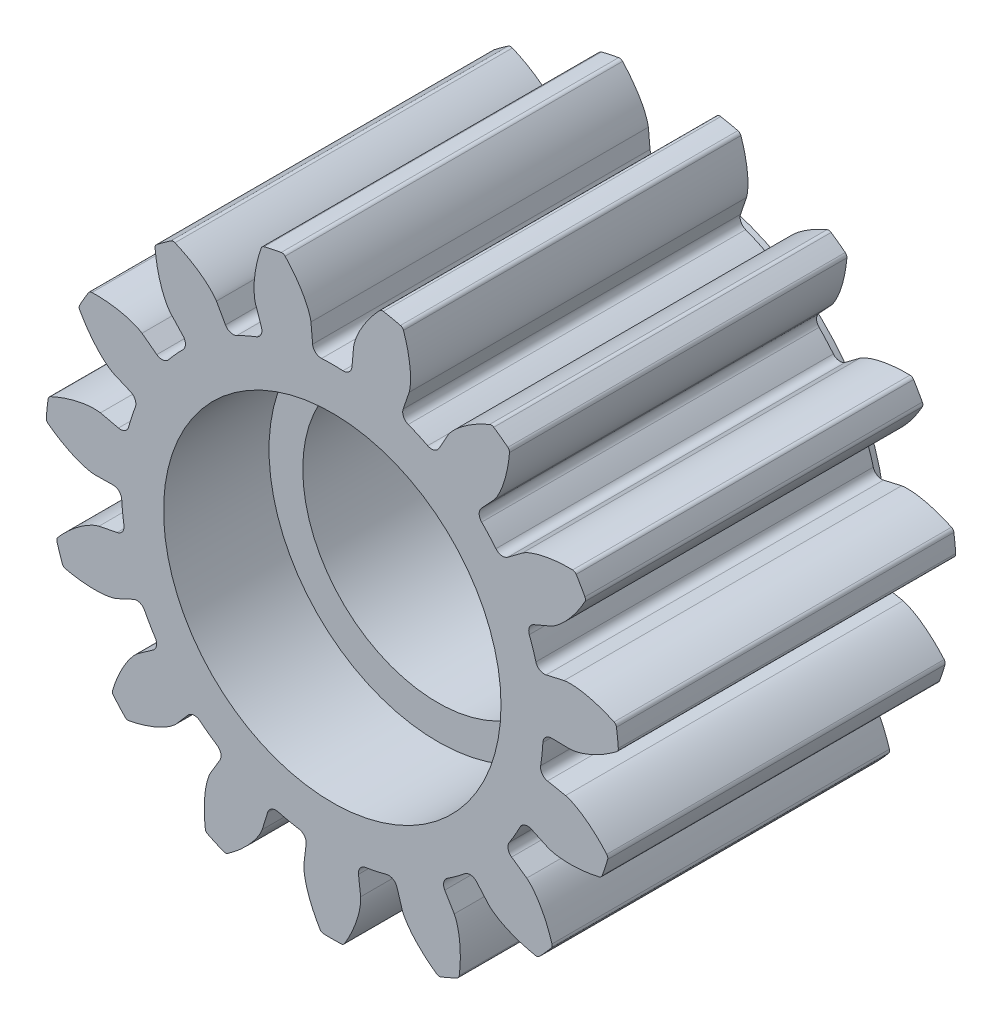
SolidWorks part; units mm, degrees
material "Alloy Steel"
ref_plane "Front" through (0, 0, 0) normal (0, 0, 1) x (1, 0, 0)
ref_plane "Top" through (0, 0, 0) normal (0, 1, 0) x (1, 0, 0)
ref_plane "Right" through (0, 0, 0) normal (1, 0, 0) x (0, 0, -1)
sketch "Sketch1" plane through (0, 0, 0) normal (0, 0, 1) x (1, 0, 0)
  circle A0 centre (0, 0) radius 10.795
  dimension "OutsideDiameter" = 21.59
extrude "Boss-Extrude1" add sketch "Sketch1" along normal blind 12.7
sketch "Sketch3" plane through (0, 0, 0) normal (0, 0, 1) x (1, 0, 0)
  line L0 (0, 0) -> (43.7181, 0) construction
  line L2 (0, 0) -> (-0.712, 7.9055) construction
  line L3 (0, 0) -> (0.712, 7.9055) construction
  line L4 (0.712, 7.9055) -> (0.8028, 8.9145) construction
  line L5 (0, 0) -> (0, 61.276) construction
  line L6 (-0.712, 7.9055) -> (-0.8028, 8.9145) construction
  circle A0 centre (0, 0) radius 10.795 construction
  circle A1 centre (0, 0) radius 9.525 construction
  circle A2 centre (0, 0) radius 8.9506 construction
  arc A3 (0.712, 7.9055) -> (-0.712, 7.9055) centre (0, 0) ccw construction
  arc A5 (1.8351, 10.6379) -> (-1.8351, 10.6379) centre (0, 0) ccw
  spline S0 degree 4 poles (-0.8028, 8.9145) (-0.8031, 8.9175) (-0.8041, 8.9259) (-0.8066, 8.9416) (-0.8113, 8.9673) (-0.8183, 8.9998) (-0.8287, 9.0417) (-0.8426, 9.0906) (-0.8594, 9.1441) (-0.8795, 9.2019) (-0.9011, 9.2592) (-0.9242, 9.316) (-0.9484, 9.3722) (-0.9793, 9.4398) (-1.0185, 9.5203) (-1.0674, 9.6134) (-1.1265, 9.7178) (-1.1905, 9.8228) (-1.2566, 9.925) (-1.327, 10.0269) (-1.3976, 10.1244) (-1.4745, 10.2242) (-1.5473, 10.3155) (-1.6328, 10.416) (-1.7029, 10.4966) (-1.7995, 10.6009) (-1.8578, 10.6619) (-1.9274, 10.7325) (-1.9591, 10.7635) (-1.9785, 10.7826) knots 0 0 0 0 0 0.005377 0.015084 0.028532 0.04661 0.064855 0.092111 0.119476 0.146842 0.174209 0.201575 0.228941 0.256307 0.307035 0.361767 0.4165 0.471232 0.525964 0.580697 0.635429 0.690161 0.744894 0.799626 0.854358 0.909091 0.954545 1 1 1 1 1 construction
  spline S1 degree 4 poles (-0.8028, 8.9145) (-0.8031, 8.9175) (-0.8041, 8.9259) (-0.8066, 8.9416) (-0.8113, 8.9673) (-0.8183, 8.9998) (-0.8287, 9.0417) (-0.8426, 9.0906) (-0.8594, 9.1441) (-0.8795, 9.2019) (-0.9011, 9.2592) (-0.9242, 9.316) (-0.9484, 9.3722) (-0.9793, 9.4398) (-1.0185, 9.5203) (-1.0674, 9.6134) (-1.1265, 9.7178) (-1.1905, 9.8228) (-1.2566, 9.925) (-1.327, 10.0269) (-1.3976, 10.1244) (-1.4745, 10.2242) (-1.5473, 10.3155) (-1.6328, 10.416) (-1.7029, 10.4966) (-1.7786, 10.5782) (-1.8159, 10.6178) (-1.8351, 10.6379) knots 0 0 0 0 0 0.005377 0.015084 0.028532 0.04661 0.064855 0.092111 0.119476 0.146842 0.174209 0.201575 0.228941 0.256307 0.307035 0.361767 0.4165 0.471232 0.525964 0.580697 0.635429 0.690161 0.744894 0.799626 0.854358 0.909091 0.909091 0.909091 0.909091 0.909091
  spline S2 degree 4 poles (0.8028, 8.9145) (0.8031, 8.9175) (0.8041, 8.9259) (0.8066, 8.9416) (0.8113, 8.9673) (0.8183, 8.9998) (0.8287, 9.0417) (0.8426, 9.0906) (0.8594, 9.1441) (0.8795, 9.2019) (0.9011, 9.2592) (0.9242, 9.316) (0.9484, 9.3722) (0.9793, 9.4398) (1.0185, 9.5203) (1.0674, 9.6134) (1.1265, 9.7178) (1.1905, 9.8228) (1.2566, 9.925) (1.327, 10.0269) (1.3976, 10.1244) (1.4745, 10.2242) (1.5473, 10.3155) (1.6328, 10.416) (1.7029, 10.4966) (1.7995, 10.6009) (1.8578, 10.6619) (1.9274, 10.7325) (1.9591, 10.7635) (1.9785, 10.7826) knots 0 0 0 0 0 0.005377 0.015084 0.028532 0.04661 0.064855 0.092111 0.119476 0.146842 0.174209 0.201575 0.228941 0.256307 0.307035 0.361767 0.4165 0.471232 0.525964 0.580697 0.635429 0.690161 0.744894 0.799626 0.854358 0.909091 0.954545 1 1 1 1 1 construction
  spline S3 degree 4 poles (0.8028, 8.9145) (0.8031, 8.9175) (0.8041, 8.9259) (0.8066, 8.9416) (0.8113, 8.9673) (0.8183, 8.9998) (0.8287, 9.0417) (0.8426, 9.0906) (0.8594, 9.1441) (0.8795, 9.2019) (0.9011, 9.2592) (0.9242, 9.316) (0.9484, 9.3722) (0.9793, 9.4398) (1.0185, 9.5203) (1.0674, 9.6134) (1.1265, 9.7178) (1.1905, 9.8228) (1.2566, 9.925) (1.327, 10.0269) (1.3976, 10.1244) (1.4745, 10.2242) (1.5473, 10.3155) (1.6328, 10.416) (1.7029, 10.4966) (1.7786, 10.5782) (1.8159, 10.6178) (1.8351, 10.6379) knots 0 0 0 0 0 0.005377 0.015084 0.028532 0.04661 0.064855 0.092111 0.119476 0.146842 0.174209 0.201575 0.228941 0.256307 0.307035 0.361767 0.4165 0.471232 0.525964 0.580697 0.635429 0.690161 0.744894 0.799626 0.854358 0.909091 0.909091 0.909091 0.909091 0.909091
  dimension "OutsideDiameter" = 21.59
  dimension "PitchCircle" = 19.05
  dimension "BaseCircle" = 17.9011
  dimension "DedendumCircle" = 15.875
sketch "DCLTBC" plane through (0, 0, 0) normal (0, 0, 1) x (1, 0, 0)
  line L0 (0, 0) -> (41.04, 0) construction
  line L1 (-0.712, 7.9055) -> (-0.8028, 8.9145) construction
  line L2 (0.712, 7.9055) -> (0.8028, 8.9145) construction
  line L3 (-0.7404, 8.2217) -> (-0.8028, 8.9145)
  line L4 (0.7404, 8.2217) -> (0.8028, 8.9145)
  line L5 (0, 0) -> (0, 104.9356) construction
  circle A0 centre (0, 0) radius 10.795
  circle A1 centre (0, 0) radius 9.525 construction
  circle A2 centre (0, 0) radius 8.9506 construction
  arc A3 (0.712, 7.9055) -> (-0.712, 7.9055) centre (0, 0) ccw construction
  arc A4 (0.4015, 7.9273) -> (-0.4015, 7.9273) centre (0, 0) ccw
  arc A5 (-0.7404, 8.2217) -> (-0.4015, 7.9273) centre (-0.4179, 8.2508) ccw
  arc A7 (0.7404, 8.2217) -> (0.4015, 7.9273) centre (0.4179, 8.2508) cw
  spline S0 degree 4 poles (-995.1793, -96.8983) (-12.295, 6.8209) (-0.9092, 8.2064) (-0.7443, 8.6021) (-0.8113, 8.9673) (-0.8183, 8.9998) (-0.8287, 9.0417) (-0.8426, 9.0906) (-0.8594, 9.1441) (-0.8795, 9.2019) (-0.9011, 9.2592) (-0.9242, 9.316) (-0.9484, 9.3722) (-0.9793, 9.4398) (-1.0185, 9.5203) (-1.0674, 9.6134) (-1.1265, 9.7178) (-1.1905, 9.8228) (-1.2566, 9.925) (-1.327, 10.0269) (-1.3976, 10.1244) (-1.4745, 10.2242) (-1.5473, 10.3155) (-1.6328, 10.416) (-2.006, 10.8448) (-3.4164, 12.2251) (15.2695, -7.4447) (-693.9148, 732.4306) knots -0.616876 -0.616876 -0.616876 -0.616876 -0.616876 0.005377 0.015084 0.028532 0.04661 0.064855 0.092111 0.119476 0.146842 0.174209 0.201575 0.228941 0.256307 0.307035 0.361767 0.4165 0.471232 0.525964 0.580697 0.635429 0.690161 0.744894 0.799626 0.854358 1.855242 1.855242 1.855242 1.855242 1.855242 only from (-0.8028, 8.9145) to (-1.8351, 10.6379) construction
  spline S1 degree 4 poles (995.1793, -96.8983) (12.295, 6.8209) (0.9092, 8.2064) (0.7443, 8.6021) (0.8113, 8.9673) (0.8183, 8.9998) (0.8287, 9.0417) (0.8426, 9.0906) (0.8594, 9.1441) (0.8795, 9.2019) (0.9011, 9.2592) (0.9242, 9.316) (0.9484, 9.3722) (0.9793, 9.4398) (1.0185, 9.5203) (1.0674, 9.6134) (1.1265, 9.7178) (1.1905, 9.8228) (1.2566, 9.925) (1.327, 10.0269) (1.3976, 10.1244) (1.4745, 10.2242) (1.5473, 10.3155) (1.6328, 10.416) (2.006, 10.8448) (3.4164, 12.2251) (-15.2695, -7.4447) (693.9148, 732.4306) knots -0.616876 -0.616876 -0.616876 -0.616876 -0.616876 0.005377 0.015084 0.028532 0.04661 0.064855 0.092111 0.119476 0.146842 0.174209 0.201575 0.228941 0.256307 0.307035 0.361767 0.4165 0.471232 0.525964 0.580697 0.635429 0.690161 0.744894 0.799626 0.854358 1.855242 1.855242 1.855242 1.855242 1.855242 only from (0.8028, 8.9145) to (1.8351, 10.6379) construction
  spline S2 degree 4 poles (-0.8028, 8.9145) (-0.8031, 8.9175) (-0.8041, 8.9259) (-0.8066, 8.9416) (-0.8113, 8.9673) (-0.8183, 8.9998) (-0.8287, 9.0417) (-0.8426, 9.0906) (-0.8594, 9.1441) (-0.8795, 9.2019) (-0.9011, 9.2592) (-0.9242, 9.316) (-0.9484, 9.3722) (-0.9793, 9.4398) (-1.0185, 9.5203) (-1.0674, 9.6134) (-1.1265, 9.7178) (-1.1905, 9.8228) (-1.2566, 9.925) (-1.327, 10.0269) (-1.3976, 10.1244) (-1.4745, 10.2242) (-1.5473, 10.3155) (-1.6328, 10.416) (-1.7029, 10.4966) (-1.7786, 10.5782) (-1.8159, 10.6178) (-1.8351, 10.6379) knots 0 0 0 0 0 0.005377 0.015084 0.028532 0.04661 0.064855 0.092111 0.119476 0.146842 0.174209 0.201575 0.228941 0.256307 0.307035 0.361767 0.4165 0.471232 0.525964 0.580697 0.635429 0.690161 0.744894 0.799626 0.854358 0.909091 0.909091 0.909091 0.909091 0.909091
  spline S3 degree 4 poles (0.8028, 8.9145) (0.8031, 8.9175) (0.8041, 8.9259) (0.8066, 8.9416) (0.8113, 8.9673) (0.8183, 8.9998) (0.8287, 9.0417) (0.8426, 9.0906) (0.8594, 9.1441) (0.8795, 9.2019) (0.9011, 9.2592) (0.9242, 9.316) (0.9484, 9.3722) (0.9793, 9.4398) (1.0185, 9.5203) (1.0674, 9.6134) (1.1265, 9.7178) (1.1905, 9.8228) (1.2566, 9.925) (1.327, 10.0269) (1.3976, 10.1244) (1.4745, 10.2242) (1.5473, 10.3155) (1.6328, 10.416) (1.7029, 10.4966) (1.7786, 10.5782) (1.8159, 10.6178) (1.8351, 10.6379) knots 0 0 0 0 0 0.005377 0.015084 0.028532 0.04661 0.064855 0.092111 0.119476 0.146842 0.174209 0.201575 0.228941 0.256307 0.307035 0.361767 0.4165 0.471232 0.525964 0.580697 0.635429 0.690161 0.744894 0.799626 0.854358 0.909091 0.909091 0.909091 0.909091 0.909091
  dimension "OutsideDiameter" = 21.59
  dimension "PitchCircle" = 19.05
  dimension "BaseCircle" = 17.9011
  dimension "D1" = 0.3238
extrude "Cut-Extrude-DCLTBC" cut sketch "DCLTBC" along normal through all contours L4 S3 A0 S2 L3 A5 A4 A7
fillet "Fillet-DCLTBC" radius 0.1619 2 edges at (1.8351, 10.6379, 6.35) (-1.8351, 10.6379, 6.35)
pattern_circular "CirPattern-DCLTBC" count 15 over 360 about axis through (0, 0, 12.7) along (0, 0, 1) of "Cut-Extrude-DCLTBC", "Fillet-DCLTBC"
sketch "DCGTBC" [suppressed] plane through (0, 0, 0) normal (0, 0, 1) x (1, 0, 0)
  line L0 (0, 0) -> (41.04, 0) construction
  line L5 (0, 0) -> (0, 104.9356) construction
  circle A0 centre (0, 0) radius 33.02
  circle A1 centre (0, 0) radius 31.75 construction
  circle A2 centre (0, 0) radius 29.8352 construction
  arc A3 (0.498, 30.1584) -> (-0.498, 30.1584) centre (0, 0) ccw construction
  arc A5 (0.2614, 30.1614) -> (0.5806, 30.4159) centre (0.2642, 30.4852) ccw
  arc A7 (-0.5806, 30.4159) -> (-0.2614, 30.1614) centre (-0.2642, 30.4852) ccw
  arc A11 (0.2614, 30.1614) -> (-0.2614, 30.1614) centre (0, 0) ccw
  spline S2 degree 4 poles (-999.5536, -12.7278) (-12.5544, 28.0053) (-0.6553, 28.7383) (-0.4506, 29.3302) (-0.4983, 29.9192) (-0.504, 29.9738) (-0.5128, 30.0443) (-0.5251, 30.1273) (-0.5406, 30.2184) (-0.5595, 30.3176) (-0.5803, 30.4164) (-0.6028, 30.5149) (-0.6268, 30.6129) (-0.6577, 30.7316) (-0.6973, 30.8738) (-0.7475, 31.0397) (-0.8089, 31.2277) (-0.8762, 31.4191) (-0.9464, 31.6071) (-1.0218, 31.7967) (-1.098, 31.98) (-1.1818, 32.1701) (-1.2615, 32.3454) (-1.3559, 32.5413) (-1.7288, 33.2996) (-3.049, 35.6508) (11.5222, 8.1522) (-473.0995, 914.7978) knots -0.593942 -0.593942 -0.593942 -0.593942 -0.593942 0.005377 0.015084 0.028532 0.04661 0.064855 0.092111 0.119476 0.146842 0.174209 0.201575 0.228941 0.256307 0.307035 0.361767 0.4165 0.471232 0.525964 0.580697 0.635429 0.690161 0.744894 0.799626 0.854358 1.740449 1.740449 1.740449 1.740449 1.740449 only from (-0.4926, 29.8312) to (-1.5817, 32.9821) construction
  spline S3 degree 4 poles (999.5536, -12.7278) (12.5544, 28.0053) (0.6553, 28.7383) (0.4506, 29.3302) (0.4983, 29.9192) (0.504, 29.9738) (0.5128, 30.0443) (0.5251, 30.1273) (0.5406, 30.2184) (0.5595, 30.3176) (0.5803, 30.4164) (0.6028, 30.5149) (0.6268, 30.6129) (0.6577, 30.7316) (0.6973, 30.8738) (0.7475, 31.0397) (0.8089, 31.2277) (0.8762, 31.4191) (0.9464, 31.6071) (1.0218, 31.7967) (1.098, 31.98) (1.1818, 32.1701) (1.2615, 32.3454) (1.3559, 32.5413) (1.7288, 33.2996) (3.049, 35.6508) (-11.5222, 8.1522) (473.0995, 914.7978) knots -0.593942 -0.593942 -0.593942 -0.593942 -0.593942 0.005377 0.015084 0.028532 0.04661 0.064855 0.092111 0.119476 0.146842 0.174209 0.201575 0.228941 0.256307 0.307035 0.361767 0.4165 0.471232 0.525964 0.580697 0.635429 0.690161 0.744894 0.799626 0.854358 1.740449 1.740449 1.740449 1.740449 1.740449 only from (0.4926, 29.8312) to (1.5817, 32.9821) construction
  spline S4 degree 4 poles (-0.5806, 30.4159) (-0.5833, 30.4283) (-0.5915, 30.4654) (-0.6058, 30.527) (-0.6268, 30.6129) (-0.6577, 30.7316) (-0.6973, 30.8738) (-0.7475, 31.0397) (-0.8089, 31.2277) (-0.8762, 31.4191) (-0.9464, 31.6071) (-1.0218, 31.7967) (-1.098, 31.98) (-1.1818, 32.1701) (-1.2615, 32.3454) (-1.3559, 32.5413) (-1.4337, 32.6994) (-1.5183, 32.8623) (-1.5601, 32.9416) (-1.5817, 32.9821) knots 0.160405 0.160405 0.160405 0.160405 0.160405 0.174209 0.201575 0.228941 0.256307 0.307035 0.361767 0.4165 0.471232 0.525964 0.580697 0.635429 0.690161 0.744894 0.799626 0.854358 0.909091 0.909091 0.909091 0.909091 0.909091
  spline S5 degree 4 poles (0.5806, 30.4159) (0.5833, 30.4283) (0.5915, 30.4654) (0.6058, 30.527) (0.6268, 30.6129) (0.6577, 30.7316) (0.6973, 30.8738) (0.7475, 31.0397) (0.8089, 31.2277) (0.8762, 31.4191) (0.9464, 31.6071) (1.0218, 31.7967) (1.098, 31.98) (1.1818, 32.1701) (1.2615, 32.3454) (1.3559, 32.5413) (1.4337, 32.6994) (1.5183, 32.8623) (1.5601, 32.9416) (1.5817, 32.9821) knots 0.160405 0.160405 0.160405 0.160405 0.160405 0.174209 0.201575 0.228941 0.256307 0.307035 0.361767 0.4165 0.471232 0.525964 0.580697 0.635429 0.690161 0.744894 0.799626 0.854358 0.909091 0.909091 0.909091 0.909091 0.909091
  dimension "OutsideDiameter" = 21.59
  dimension "PitchCircle" = 19.05
  dimension "BaseCircle" = 17.9011
  dimension "D1" = 0.3238
extrude "Cut-Extrude-DCGTBC" [suppressed] cut sketch "DCGTBC" along normal through all contours A5 S5 A0 S4 A7 A11
fillet "Fillet-DCGTBC" [suppressed] radius 0.1619
pattern_circular "CirPattern-DCGTBC" [suppressed] count 15 over 360
sketch "Sketch4" plane through (0, 0, 12.7) normal (0, 0, 1) x (1, 0, 0)
  circle A0 centre (0, 0) radius 4.7625
  dimension "D1" = 9.525
extrude "Cut-Extrude2" cut sketch "Sketch4" against normal through all
sketch "Sketch5" plane through (0, 0, 12.7) normal (0, 0, 1) x (1, 0, 0)
  circle A0 centre (0, 0) radius 6.35
  dimension "D1" = 12.7
extrude "Cut-Extrude3" cut sketch "Sketch5" against normal blind 3.9688
sketch "Sketch6" plane through (0, 0, 8.7312) normal (0, 0, 1) x (1, 0, 0)
  circle A0 centre (0, 0) radius 5.08
  dimension "D1" = 10.16
extrude "Cut-Extrude4" cut sketch "Sketch6" against normal through all
sketch "Sketch7" plane through (0, 0, 0) normal (0, 0, -1) x (-1, 0, 0)
  circle A0 centre (0, 0) radius 5.08 construction
  circle A1 centre (0, 0) radius 5.08
  circle A2 centre (0, 0) radius 7.874
  dimension "D1" = 15.748
extrude "Boss-Extrude2" add sketch "Sketch7" along normal blind 0.254
equation "\"DiametralPitch\"= 20'Diametral Pitch"
equation "\"NumTeeth\"= 15'Number of Teeth"
equation "\"PressureAngle\"= 20deg'Pressure Angle"
equation "\"Addendum\"= 1 / \"DiametralPitch\"'Addendum"
equation "\"Dedendum\"= 1.25 / \"DiametralPitch\"'Dedendum"
equation "\"WorkingDepth\"= 2 / \"DiametralPitch\"'Working Depth - here for REF (Not used in building model)"
equation "\"WholeDepth\"= 2.25 / \"DiametralPitch\"'Whole Depth - here for REF (Not used in building model)"
equation "\"Clearance\"= .19 / \"DiametralPitch\"'Clearance"
equation "\"CircularPitch\"= pi / \"DiametralPitch\"'Circular Pitch - here for REF (Not used in building model)"
equation "\"PitchCircle\"= \"NumTeeth\" / \"DiametralPitch\"'Pitch Circle - or - Pitch Diameter"
equation "\"OutsideDiameter\"= ( \"NumTeeth\" + 2 ) / \"DiametralPitch\"'Outside Diameter"
equation "\"Fillet\"= \"Clearance\" * cos ( \"PressureAngle\" ) * tan ( ( 90 + \"PressureAngle\" ) / 2 )'Fillet"
equation "\"AddendumCircle\"= \"PitchCircle\" + ( 2 * \"Addendum\" )'Addendum Circle - or - Addendum Diameter"
equation "\"DedendumCircle\"= \"PitchCircle\" - ( 2 * \"Dedendum\" )'Dedendum Circle - or - Dedendum Diameter"
equation "\"BaseCircle\"= \"PitchCircle\" * cos ( \"PressureAngle\" )'Base Circle - Base Diameter"
equation "\"PitchAngle\"= 360deg / \"NumTeeth\"'Pitch Angle"
equation "\"Alpha\"= sqr ( \"PitchCircle\" ^ 2 - \"BaseCircle\" ^ 2 ) / \"BaseCircle\" * 180 / PI - \"PressureAngle\"'Alpha - Used for Calculating Beta"
equation "\"Beta\"= ( \"PitchAngle\" / 4 - ( \"Alpha\" - 90 ) )'Beta - Used in definition of the parameters for the parametric equation driven curve"
equation "\"Gamma\"= ( \"PitchAngle\" / 4 - ( \"Alpha\" + 90 ) )'Gamma - Used in definition of the parameters for the parametric equation driven curve"
equation "\"Phi\"= sqr ( ( \"AddendumCircle\" / 2 ) ^ 2 - ( \"BaseCircle\" / 2 ) ^ 2 ) / ( \"BaseCircle\" / 2 )'Phi - Used in definition of the parameters for the parametric equation driven curve"
equation "\"DCGTBC\"= iif ( ( \"DedendumCircle\" + ( \"Fillet\" * 2 ) ) > \"BaseCircle\" , \"unsuppressed\" , \"suppressed\" )'if Dedendum Circle +2X Fillet IS GREATER THAN BaseCircle THEN Unsuppress OR Suppress FEATURE"
equation "\"DCLTBC\"= iif ( ( \"DedendumCircle\" + ( \"Fillet\" * 2 ) ) > \"BaseCircle\" , \"suppressed\" , \"unsuppressed\" )'if Dedendum Circle +2X Fillet IS GREATER THAN BaseCircle THEN Suppress OR Unsuppress FEATURE"
equation "\"Cut-Extrude-DCGTBC\"= iif ( ( \"DedendumCircle\" + ( \"Fillet\" * 2 ) ) > \"BaseCircle\" , \"unsuppressed\" , \"suppressed\" )'if Dedendum Circle +2X Fillet IS GREATER THAN BaseCircle THEN UnsuppressORSuppress FEATURE"
equation "\"Cut-Extrude-DCLTBC\"= iif ( ( \"DedendumCircle\" + ( \"Fillet\" * 2 ) ) > \"BaseCircle\" , \"suppressed\" , \"unsuppressed\" )'if Dedendum Circle +2X Fillet IS GREATER THAN BaseCircle THEN SuppressORUnsuppress FEATURE"
equation "\"CirPattern-DCGTBC\"= iif ( ( \"DedendumCircle\" + ( \"Fillet\" * 2 ) ) > \"BaseCircle\" , \"unsuppressed\" , \"suppressed\" )'if Dedendum Circle +2X Fillet IS GREATER THAN \"BaseCircle\" THEN UnsuppressORSuppress FEATURE"
equation "\"CirPattern-DCLTBC\"= iif ( ( \"DedendumCircle\" + ( \"Fillet\" * 2 ) ) > \"BaseCircle\" , \"suppressed\" , \"unsuppressed\" )'if Dedendum Circle +2X Fillet IS GREATER THAN \"BaseCircle\" THEN SuppressORUnsuppress FEATURE"
equation "\"Fillet-DCGTBC\"= iif ( ( \"DedendumCircle\" + ( \"Fillet\" * 2 ) ) > \"BaseCircle\" , \"unsuppressed\" , \"suppressed\" )'if Dedendum Circle +2X Fillet IS GREATER THAN \"BaseCircle\" THEN UnsuppressORSuppress FEATURE"
equation "\"Fillet-DCLTBC\"= iif ( ( \"DedendumCircle\" + ( \"Fillet\" * 2 ) ) > \"BaseCircle\" , \"suppressed\" , \"unsuppressed\" )'if Dedendum Circle +2X Fillet IS GREATER THAN \"BaseCircle\" THEN SuppressORUnsuppress FEATURE"
equation "\"D1@CirPattern-DCGTBC\"=\"NumTeeth\""
equation "\"D1@CirPattern-DCLTBC\"=\"NumTeeth\""
equation "\"D1@DCGTBC\"=\"Fillet\""
equation "\"D1@DCLTBC\"=\"Fillet\""
equation "\"D1@Fillet-DCLTBC\"=\"Fillet\"/2"
equation "\"D1@Fillet-DCGTBC\"=\"Fillet\"/2"
